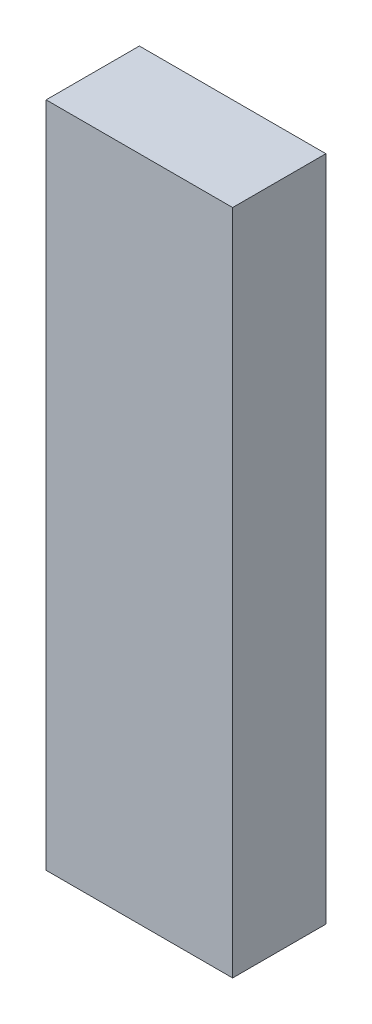
SolidWorks part; units mm, degrees
ref_plane "Front Plane" through (0, 0, 0) normal (0, 0, 1) x (1, 0, 0)
ref_plane "Top Plane" through (0, 0, 0) normal (0, 1, 0) x (1, 0, 0)
ref_plane "Right Plane" through (0, 0, 0) normal (1, 0, 0) x (0, 0, -1)
sketch "Sketch1" plane through (0, 0, 0) normal (0, 1, 0) x (1, 0, 0)
  line L0 (-50.8, 25.4) -> (50.8, -25.4) construction
  line L1 (-50.8, 25.4) -> (50.8, 25.4)
  line L2 (-50.8, 25.4) -> (-50.8, -25.4)
  line L3 (-50.8, -25.4) -> (50.8, -25.4)
  line L4 (50.8, 25.4) -> (50.8, -25.4)
  dimension "D1" = 101.6
  dimension "D2" = 50.8
extrude "Boss-Extrude1" add sketch "Sketch1" along normal blind 363.474
